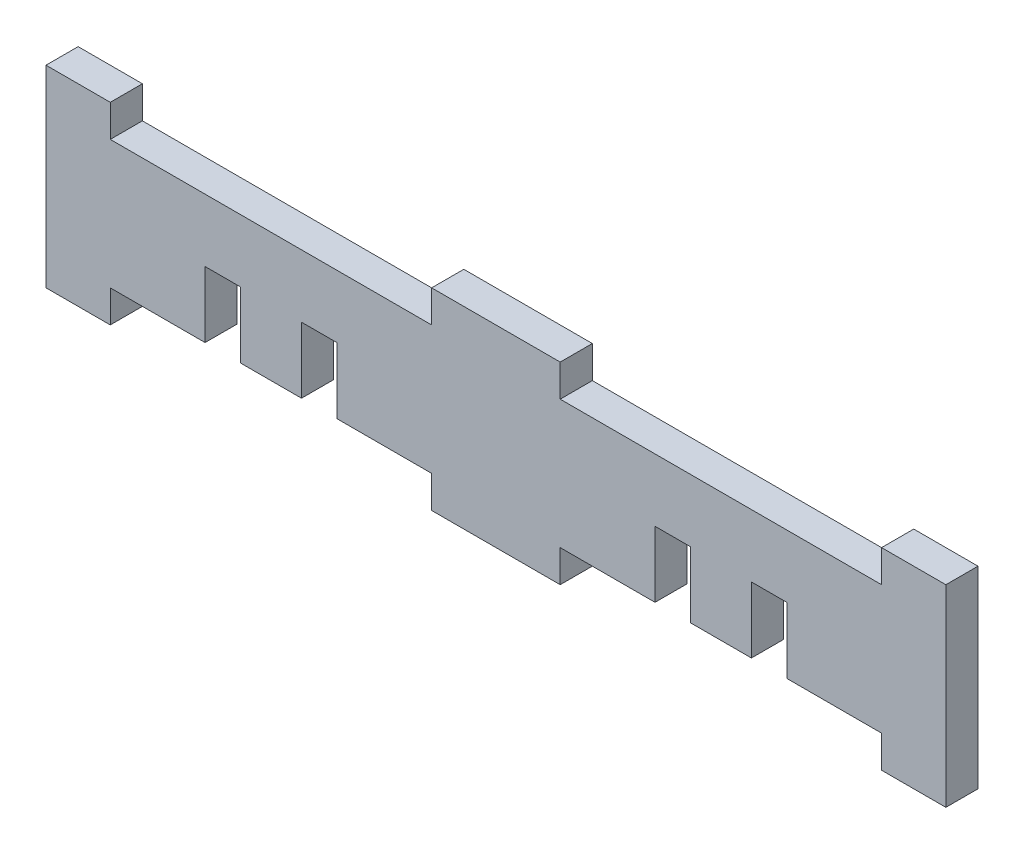
SolidWorks part; units mm, degrees
ref_plane "Front Plane" through (0, 0, 0) normal (0, 0, 1) x (1, 0, 0)
ref_plane "Top Plane" through (0, 0, 0) normal (0, 1, 0) x (1, 0, 0)
ref_plane "Right Plane" through (0, 0, 0) normal (1, 0, 0) x (0, 0, -1)
sketch "Model" plane through (0, 0, 0) normal (0, 0, 1) x (1, 0, 0)
  line L0 (-1336.4543, -207.297) -> (-1321.7043, -207.297)
  line L1 (-1386.2043, -207.297) -> (-1376.7043, -207.297)
  line L2 (-1316.2043, -207.297) -> (-1316.2043, -197.047)
  line L3 (-1276.4543, -182.297) -> (-1286.4543, -182.297)
  line L4 (-1316.2043, -197.047) -> (-1321.7043, -197.047)
  line L5 (-1306.7043, -197.047) -> (-1306.7043, -207.297)
  line L6 (-1301.2043, -197.047) -> (-1306.7043, -197.047)
  line L7 (-1371.2043, -207.297) -> (-1356.4543, -207.297)
  line L8 (-1276.4543, -212.297) -> (-1276.4543, -182.297)
  line L9 (-1356.4543, -207.297) -> (-1356.4543, -212.297)
  line L10 (-1406.4543, -182.297) -> (-1416.4543, -182.297)
  line L11 (-1376.7043, -197.047) -> (-1376.7043, -207.297)
  line L12 (-1391.7043, -197.047) -> (-1391.7043, -207.297)
  line L13 (-1286.4543, -187.297) -> (-1336.4543, -187.297)
  line L14 (-1286.4543, -182.297) -> (-1286.4543, -187.297)
  line L15 (-1406.4543, -207.297) -> (-1391.7043, -207.297)
  line L16 (-1301.2043, -207.297) -> (-1301.2043, -197.047)
  line L17 (-1406.4543, -187.297) -> (-1406.4543, -182.297)
  line L18 (-1336.4543, -182.297) -> (-1356.4543, -182.297)
  line L19 (-1286.4543, -212.297) -> (-1276.4543, -212.297)
  line L20 (-1386.2043, -197.047) -> (-1391.7043, -197.047)
  line L21 (-1371.2043, -207.297) -> (-1371.2043, -197.047)
  line L22 (-1356.4543, -187.297) -> (-1406.4543, -187.297)
  line L23 (-1416.4543, -212.297) -> (-1406.4543, -212.297)
  line L24 (-1356.4543, -182.297) -> (-1356.4543, -187.297)
  line L25 (-1356.4543, -212.297) -> (-1336.4543, -212.297)
  line L26 (-1301.2043, -207.297) -> (-1286.4543, -207.297)
  line L27 (-1371.2043, -197.047) -> (-1376.7043, -197.047)
  line L28 (-1321.7043, -197.047) -> (-1321.7043, -207.297)
  line L29 (-1316.2043, -207.297) -> (-1306.7043, -207.297)
  line L30 (-1286.4543, -207.297) -> (-1286.4543, -212.297)
  line L31 (-1336.4543, -187.297) -> (-1336.4543, -182.297)
  line L32 (-1416.4543, -182.297) -> (-1416.4543, -212.297)
  line L33 (-1406.4543, -212.297) -> (-1406.4543, -207.297)
  line L34 (-1386.2043, -207.297) -> (-1386.2043, -197.047)
  line L35 (-1336.4543, -212.297) -> (-1336.4543, -207.297)
  line L36 (-1411.4543, -205.297) -> (-1411.4543, -210.297)
  line L37 (-1412.4543, -208.297) -> (-1411.4543, -210.297)
  line L38 (-1410.4543, -208.297) -> (-1411.4543, -210.297)
  line L39 (-1408.3949, -204.2749) -> (-1407.783, -201.7779)
  line L40 (-1414.0103, -199.996) -> (-1413.6489, -200.1014)
  line L41 (-1412.4518, -200.3453) -> (-1412.3909, -200.2559)
  line L42 (-1412.1474, -200.0983) -> (-1412.3909, -200.2559)
  line L43 (-1413.3475, -200.3455) -> (-1413.4078, -200.2567)
  line L44 (-1414.4513, -199.9609) -> (-1414.0103, -199.996)
  line L45 (-1409.5188, -199.9609) -> (-1409.0443, -201.7779)
  line L46 (-1411.7915, -199.9953) -> (-1411.3482, -199.9609)
  line L47 (-1411.3482, -204.2688) -> (-1411.7821, -204.233)
  line L48 (-1412.3909, -203.9692) -> (-1412.1474, -204.1253)
  line L49 (-1410.3304, -204.2688) -> (-1411.3482, -204.2688)
  line L50 (-1412.1474, -200.0983) -> (-1411.7915, -199.9953)
  line L51 (-1412.4721, -203.7881) -> (-1412.4518, -203.8817)
  line L52 (-1411.3482, -199.9609) -> (-1410.3304, -199.9609)
  line L53 (-1412.4721, -203.7881) -> (-1412.4721, -200.4417)
  line L54 (-1413.4078, -200.2567) -> (-1413.6489, -200.1014)
  line L55 (-1412.1474, -204.1253) -> (-1411.7821, -204.233)
  line L56 (-1413.3274, -200.4417) -> (-1413.3475, -200.3455)
  line L57 (-1412.3909, -203.9692) -> (-1412.4518, -203.8817)
  line L58 (-1410.3304, -204.2688) -> (-1410.3304, -199.9609)
  line L59 (-1409.0443, -201.7779) -> (-1408.3949, -204.2749)
  line L60 (-1409.0443, -201.7779) -> (-1407.783, -201.7779)
  line L61 (-1412.4721, -200.4417) -> (-1412.4518, -200.3453)
  line L62 (-1414.8923, -199.996) -> (-1414.4513, -199.9609)
  line L63 (-1415.5551, -202.2485) -> (-1415.5752, -202.1523)
  line L64 (-1415.5752, -200.4417) -> (-1415.5551, -200.3455)
  line L65 (-1415.5003, -204.2688) -> (-1413.3274, -204.2688)
  line L66 (-1415.4948, -200.2567) -> (-1415.2536, -200.1014)
  line L67 (-1415.5551, -200.3455) -> (-1415.4948, -200.2567)
  line L68 (-1413.7769, -202.5332) -> (-1414.4513, -202.6331)
  line L69 (-1415.4948, -202.3373) -> (-1415.5551, -202.2485)
  line L70 (-1413.3274, -204.2688) -> (-1413.3274, -202.1523)
  line L71 (-1414.8923, -202.598) -> (-1415.2536, -202.4926)
  line L72 (-1414.4513, -202.6331) -> (-1414.8923, -202.598)
  line L73 (-1415.2536, -200.1014) -> (-1414.8923, -199.996)
  line L74 (-1413.3274, -202.1523) -> (-1413.5459, -202.4068)
  line L75 (-1415.5752, -202.1523) -> (-1415.5752, -200.4417)
  line L76 (-1413.5459, -202.4068) -> (-1413.7769, -202.5332)
  line L77 (-1415.2536, -202.4926) -> (-1415.4948, -202.3373)
  line L78 (-1407.783, -201.7779) -> (-1407.3335, -199.9609)
  line L79 (-1284.8892, -189.3321) -> (-1284.4482, -189.297)
  line L80 (-1284.4482, -189.297) -> (-1284.0073, -189.3321)
  line L81 (-1278.398, -193.611) -> (-1277.7861, -191.114)
  line L82 (-1279.5219, -189.297) -> (-1279.0474, -191.114)
  line L83 (-1279.0474, -191.114) -> (-1277.7861, -191.114)
  line L84 (-1279.0474, -191.114) -> (-1278.398, -193.611)
  line L85 (-1283.5429, -191.7429) -> (-1283.3243, -191.4884)
  line L86 (-1283.7739, -191.8693) -> (-1284.4482, -191.9692)
  line L87 (-1283.3243, -193.6049) -> (-1285.4972, -193.6049)
  line L88 (-1283.3444, -189.6816) -> (-1283.4047, -189.5928)
  line L89 (-1283.6459, -189.4375) -> (-1284.0073, -189.3321)
  line L90 (-1285.5521, -191.5846) -> (-1285.4918, -191.6734)
  line L91 (-1285.4918, -191.6734) -> (-1285.2506, -191.8287)
  line L92 (-1283.3243, -191.4884) -> (-1283.3243, -193.6049)
  line L93 (-1283.3444, -189.6816) -> (-1283.3243, -189.7778)
  line L94 (-1283.6459, -189.4375) -> (-1283.4047, -189.5928)
  line L95 (-1283.5429, -191.7429) -> (-1283.7739, -191.8693)
  line L96 (-1284.4482, -191.9692) -> (-1284.8892, -191.9341)
  line L97 (-1285.5721, -191.4884) -> (-1285.5721, -189.7778)
  line L98 (-1285.5521, -189.6816) -> (-1285.5721, -189.7778)
  line L99 (-1285.5721, -191.4884) -> (-1285.5521, -191.5846)
  line L100 (-1285.2506, -191.8287) -> (-1284.8892, -191.9341)
  line L101 (-1277.7861, -191.114) -> (-1277.3365, -189.297)
  line L102 (-1285.4918, -189.5928) -> (-1285.2506, -189.4375)
  line L103 (-1285.2506, -189.4375) -> (-1284.8892, -189.3321)
  line L104 (-1285.5521, -189.6816) -> (-1285.4918, -189.5928)
  line L105 (-1280.7861, -191.114) -> (-1280.3365, -189.297)
  line L106 (-1282.0474, -191.114) -> (-1281.398, -193.611)
  line L107 (-1281.398, -193.611) -> (-1280.7861, -191.114)
  line L108 (-1282.5219, -189.297) -> (-1282.0474, -191.114)
  line L109 (-1282.0474, -191.114) -> (-1280.7861, -191.114)
  line L110 (-1281.4543, -189.297) -> (-1281.4543, -184.297)
  line L111 (-1280.4543, -186.297) -> (-1281.4543, -184.297)
  line L112 (-1282.4543, -186.297) -> (-1281.4543, -184.297)
  line L113 (-1414.8892, -189.3321) -> (-1414.4482, -189.297)
  line L114 (-1414.4482, -189.297) -> (-1414.0073, -189.3321)
  line L115 (-1408.398, -193.611) -> (-1407.7861, -191.114)
  line L116 (-1409.5219, -189.297) -> (-1409.0474, -191.114)
  line L117 (-1409.0474, -191.114) -> (-1407.7861, -191.114)
  line L118 (-1409.0474, -191.114) -> (-1408.398, -193.611)
  line L119 (-1413.5429, -191.7429) -> (-1413.3243, -191.4884)
  line L120 (-1413.7739, -191.8693) -> (-1414.4482, -191.9692)
  line L121 (-1413.3243, -193.6049) -> (-1415.4972, -193.6049)
  line L122 (-1413.3444, -189.6816) -> (-1413.4047, -189.5928)
  line L123 (-1413.6459, -189.4375) -> (-1414.0073, -189.3321)
  line L124 (-1415.5521, -191.5846) -> (-1415.4918, -191.6734)
  line L125 (-1415.4918, -191.6734) -> (-1415.2506, -191.8287)
  line L126 (-1413.3243, -191.4884) -> (-1413.3243, -193.6049)
  line L127 (-1413.3444, -189.6816) -> (-1413.3243, -189.7778)
  line L128 (-1413.6459, -189.4375) -> (-1413.4047, -189.5928)
  line L129 (-1413.5429, -191.7429) -> (-1413.7739, -191.8693)
  line L130 (-1414.4482, -191.9692) -> (-1414.8892, -191.9341)
  line L131 (-1415.5721, -191.4884) -> (-1415.5721, -189.7778)
  line L132 (-1415.5521, -189.6816) -> (-1415.5721, -189.7778)
  line L133 (-1415.5721, -191.4884) -> (-1415.5521, -191.5846)
  line L134 (-1415.2506, -191.8287) -> (-1414.8892, -191.9341)
  line L135 (-1407.7861, -191.114) -> (-1407.3365, -189.297)
  line L136 (-1415.4918, -189.5928) -> (-1415.2506, -189.4375)
  line L137 (-1415.2506, -189.4375) -> (-1414.8892, -189.3321)
  line L138 (-1415.5521, -189.6816) -> (-1415.4918, -189.5928)
  line L139 (-1410.7861, -191.114) -> (-1410.3365, -189.297)
  line L140 (-1412.0474, -191.114) -> (-1411.398, -193.611)
  line L141 (-1411.398, -193.611) -> (-1410.7861, -191.114)
  line L142 (-1412.5219, -189.297) -> (-1412.0474, -191.114)
  line L143 (-1412.0474, -191.114) -> (-1410.7861, -191.114)
  line L144 (-1411.4543, -189.297) -> (-1411.4543, -184.297)
  line L145 (-1410.4543, -186.297) -> (-1411.4543, -184.297)
  line L146 (-1412.4543, -186.297) -> (-1411.4543, -184.297)
  line L147 (-1281.4543, -205.297) -> (-1281.4543, -210.297)
  line L148 (-1282.4543, -208.297) -> (-1281.4543, -210.297)
  line L149 (-1280.4543, -208.297) -> (-1281.4543, -210.297)
  line L150 (-1278.3949, -204.2749) -> (-1277.783, -201.7779)
  line L151 (-1284.0103, -199.996) -> (-1283.6489, -200.1014)
  line L152 (-1282.4518, -200.3453) -> (-1282.3909, -200.2559)
  line L153 (-1282.1474, -200.0983) -> (-1282.3909, -200.2559)
  line L154 (-1283.3475, -200.3455) -> (-1283.4078, -200.2567)
  line L155 (-1284.4513, -199.9609) -> (-1284.0103, -199.996)
  line L156 (-1279.5188, -199.9609) -> (-1279.0443, -201.7779)
  line L157 (-1281.7915, -199.9953) -> (-1281.3482, -199.9609)
  line L158 (-1281.3482, -204.2688) -> (-1281.7821, -204.233)
  line L159 (-1282.3909, -203.9692) -> (-1282.1474, -204.1253)
  line L160 (-1280.3304, -204.2688) -> (-1281.3482, -204.2688)
  line L161 (-1282.1474, -200.0983) -> (-1281.7915, -199.9953)
  line L162 (-1282.4721, -203.7881) -> (-1282.4518, -203.8817)
  line L163 (-1281.3482, -199.9609) -> (-1280.3304, -199.9609)
  line L164 (-1282.4721, -203.7881) -> (-1282.4721, -200.4417)
  line L165 (-1283.4078, -200.2567) -> (-1283.6489, -200.1014)
  line L166 (-1282.1474, -204.1253) -> (-1281.7821, -204.233)
  line L167 (-1283.3274, -200.4417) -> (-1283.3475, -200.3455)
  line L168 (-1282.3909, -203.9692) -> (-1282.4518, -203.8817)
  line L169 (-1280.3304, -204.2688) -> (-1280.3304, -199.9609)
  line L170 (-1279.0443, -201.7779) -> (-1278.3949, -204.2749)
  line L171 (-1279.0443, -201.7779) -> (-1277.783, -201.7779)
  line L172 (-1282.4721, -200.4417) -> (-1282.4518, -200.3453)
  line L173 (-1284.8923, -199.996) -> (-1284.4513, -199.9609)
  line L174 (-1285.5551, -202.2485) -> (-1285.5752, -202.1523)
  line L175 (-1285.5752, -200.4417) -> (-1285.5551, -200.3455)
  line L176 (-1285.5003, -204.2688) -> (-1283.3274, -204.2688)
  line L177 (-1285.4948, -200.2567) -> (-1285.2536, -200.1014)
  line L178 (-1285.5551, -200.3455) -> (-1285.4948, -200.2567)
  line L179 (-1283.7769, -202.5332) -> (-1284.4513, -202.6331)
  line L180 (-1285.4948, -202.3373) -> (-1285.5551, -202.2485)
  line L181 (-1283.3274, -204.2688) -> (-1283.3274, -202.1523)
  line L182 (-1284.8923, -202.598) -> (-1285.2536, -202.4926)
  line L183 (-1284.4513, -202.6331) -> (-1284.8923, -202.598)
  line L184 (-1285.2536, -200.1014) -> (-1284.8923, -199.996)
  line L185 (-1283.3274, -202.1523) -> (-1283.5459, -202.4068)
  line L186 (-1285.5752, -202.1523) -> (-1285.5752, -200.4417)
  line L187 (-1283.5459, -202.4068) -> (-1283.7769, -202.5332)
  line L188 (-1285.2536, -202.4926) -> (-1285.4948, -202.3373)
  line L189 (-1277.783, -201.7779) -> (-1277.3335, -199.9609)
  line L190 (-1318.9543, -189.797) -> (-1318.9543, -194.797)
  line L191 (-1319.9543, -192.797) -> (-1318.9543, -194.797)
  line L192 (-1317.9543, -192.797) -> (-1318.9543, -194.797)
  line L193 (-1310.3564, -193.7202) -> (-1310.4162, -193.8084)
  line L194 (-1312.5032, -193.8052) -> (-1312.2597, -193.9614)
  line L195 (-1311.0218, -194.069) -> (-1310.655, -193.9614)
  line L196 (-1312.5641, -193.7178) -> (-1312.5032, -193.8052)
  line L197 (-1309.0504, -191.614) -> (-1308.401, -194.111)
  line L198 (-1311.8944, -194.069) -> (-1311.4604, -194.1049)
  line L199 (-1312.2597, -193.9614) -> (-1311.8944, -194.069)
  line L200 (-1309.5249, -189.797) -> (-1309.0504, -191.614)
  line L201 (-1311.4604, -194.1049) -> (-1311.0218, -194.069)
  line L202 (-1307.7891, -191.6197) -> (-1307.3396, -189.797)
  line L203 (-1312.5641, -193.7178) -> (-1312.5843, -193.6242)
  line L204 (-1310.3564, -193.7202) -> (-1310.3365, -193.6242)
  line L205 (-1308.401, -194.111) -> (-1307.7891, -191.6197)
  line L206 (-1307.7891, -191.6197) -> (-1309.0504, -191.614)
  line L207 (-1310.655, -193.9614) -> (-1310.4162, -193.8084)
  line L208 (-1310.4162, -190.0889) -> (-1310.655, -189.9343)
  line L209 (-1313.3274, -191.9884) -> (-1313.3274, -194.1049)
  line L210 (-1314.8923, -189.8321) -> (-1314.4513, -189.797)
  line L211 (-1310.655, -189.9343) -> (-1311.0156, -189.8313)
  line L212 (-1314.4513, -189.797) -> (-1314.0103, -189.8321)
  line L213 (-1312.5843, -193.6242) -> (-1312.5843, -193.3182)
  line L214 (-1310.3564, -190.179) -> (-1310.4162, -190.0889)
  line L215 (-1315.5551, -190.1816) -> (-1315.5752, -190.2778)
  line L216 (-1313.7769, -192.3693) -> (-1313.5459, -192.2429)
  line L217 (-1311.9038, -189.8313) -> (-1312.2597, -189.9343)
  line L218 (-1315.2537, -192.3287) -> (-1315.4948, -192.1734)
  line L219 (-1315.5752, -191.9884) -> (-1315.5752, -190.2778)
  line L220 (-1315.5551, -190.1816) -> (-1315.4948, -190.0928)
  line L221 (-1313.6489, -189.9375) -> (-1314.0103, -189.8321)
  line L222 (-1310.3365, -193.6242) -> (-1310.3365, -190.2778)
  line L223 (-1315.5752, -191.9884) -> (-1315.5551, -192.0846)
  line L224 (-1312.5843, -190.2778) -> (-1312.5843, -190.5837)
  line L225 (-1311.0156, -189.8313) -> (-1311.4604, -189.797)
  line L226 (-1315.5003, -194.1049) -> (-1313.3274, -194.1049)
  line L227 (-1315.5551, -192.0846) -> (-1315.4948, -192.1734)
  line L228 (-1314.8923, -189.8321) -> (-1315.2537, -189.9375)
  line L229 (-1313.3475, -190.1816) -> (-1313.3274, -190.2778)
  line L230 (-1312.5641, -190.1814) -> (-1312.5843, -190.2778)
  line L231 (-1313.4078, -190.0928) -> (-1313.3475, -190.1816)
  line L232 (-1312.2597, -189.9343) -> (-1312.5032, -190.092)
  line L233 (-1313.4078, -190.0928) -> (-1313.6489, -189.9375)
  line L234 (-1311.4604, -189.797) -> (-1311.9038, -189.8313)
  line L235 (-1314.4513, -192.4692) -> (-1313.7769, -192.3693)
  line L236 (-1314.8923, -192.4341) -> (-1314.4513, -192.4692)
  line L237 (-1310.3365, -190.2778) -> (-1310.3564, -190.179)
  line L238 (-1313.5459, -192.2429) -> (-1313.3274, -191.9884)
  line L239 (-1312.5032, -190.092) -> (-1312.5641, -190.1814)
  line L240 (-1315.2537, -192.3287) -> (-1314.8923, -192.4341)
  line L241 (-1315.2537, -189.9375) -> (-1315.4948, -190.0928)
  line L242 (-1303.9543, -189.797) -> (-1303.9543, -194.797)
  line L243 (-1304.9543, -192.797) -> (-1303.9543, -194.797)
  line L244 (-1302.9543, -192.797) -> (-1303.9543, -194.797)
  line L245 (-1388.9543, -189.797) -> (-1388.9543, -194.797)
  line L246 (-1389.9543, -192.797) -> (-1388.9543, -194.797)
  line L247 (-1387.9543, -192.797) -> (-1388.9543, -194.797)
  line L248 (-1380.3564, -193.7202) -> (-1380.4161, -193.8084)
  line L249 (-1382.5032, -193.8052) -> (-1382.2596, -193.9614)
  line L250 (-1381.0218, -194.069) -> (-1380.655, -193.9614)
  line L251 (-1382.564, -193.7178) -> (-1382.5032, -193.8052)
  line L252 (-1379.0504, -191.614) -> (-1378.401, -194.111)
  line L253 (-1381.8944, -194.069) -> (-1381.4604, -194.1049)
  line L254 (-1382.2596, -193.9614) -> (-1381.8944, -194.069)
  line L255 (-1379.5249, -189.797) -> (-1379.0504, -191.614)
  line L256 (-1381.4604, -194.1049) -> (-1381.0218, -194.069)
  line L257 (-1377.7891, -191.6197) -> (-1377.3396, -189.797)
  line L258 (-1382.564, -193.7178) -> (-1382.5843, -193.6242)
  line L259 (-1380.3564, -193.7202) -> (-1380.3365, -193.6242)
  line L260 (-1378.401, -194.111) -> (-1377.7891, -191.6197)
  line L261 (-1377.7891, -191.6197) -> (-1379.0504, -191.614)
  line L262 (-1380.655, -193.9614) -> (-1380.4161, -193.8084)
  line L263 (-1380.4161, -190.0889) -> (-1380.655, -189.9343)
  line L264 (-1383.3274, -191.9884) -> (-1383.3274, -194.1049)
  line L265 (-1384.8923, -189.8321) -> (-1384.4513, -189.797)
  line L266 (-1380.655, -189.9343) -> (-1381.0156, -189.8313)
  line L267 (-1384.4513, -189.797) -> (-1384.0103, -189.8321)
  line L268 (-1382.5843, -193.6242) -> (-1382.5843, -193.3182)
  line L269 (-1380.3564, -190.179) -> (-1380.4161, -190.0889)
  line L270 (-1385.5551, -190.1816) -> (-1385.5752, -190.2778)
  line L271 (-1383.7769, -192.3693) -> (-1383.5459, -192.2429)
  line L272 (-1381.9038, -189.8313) -> (-1382.2596, -189.9343)
  line L273 (-1385.2536, -192.3287) -> (-1385.4948, -192.1734)
  line L274 (-1385.5752, -191.9884) -> (-1385.5752, -190.2778)
  line L275 (-1385.5551, -190.1816) -> (-1385.4948, -190.0928)
  line L276 (-1383.6489, -189.9375) -> (-1384.0103, -189.8321)
  line L277 (-1380.3365, -193.6242) -> (-1380.3365, -190.2778)
  line L278 (-1385.5752, -191.9884) -> (-1385.5551, -192.0846)
  line L279 (-1382.5843, -190.2778) -> (-1382.5843, -190.5837)
  line L280 (-1381.0156, -189.8313) -> (-1381.4604, -189.797)
  line L281 (-1385.5003, -194.1049) -> (-1383.3274, -194.1049)
  line L282 (-1385.5551, -192.0846) -> (-1385.4948, -192.1734)
  line L283 (-1384.8923, -189.8321) -> (-1385.2536, -189.9375)
  line L284 (-1383.3475, -190.1816) -> (-1383.3274, -190.2778)
  line L285 (-1382.564, -190.1814) -> (-1382.5843, -190.2778)
  line L286 (-1383.4078, -190.0928) -> (-1383.3475, -190.1816)
  line L287 (-1382.2596, -189.9343) -> (-1382.5032, -190.092)
  line L288 (-1383.4078, -190.0928) -> (-1383.6489, -189.9375)
  line L289 (-1381.4604, -189.797) -> (-1381.9038, -189.8313)
  line L290 (-1384.4513, -192.4692) -> (-1383.7769, -192.3693)
  line L291 (-1384.8923, -192.4341) -> (-1384.4513, -192.4692)
  line L292 (-1380.3365, -190.2778) -> (-1380.3564, -190.179)
  line L293 (-1383.5459, -192.2429) -> (-1383.3274, -191.9884)
  line L294 (-1382.5032, -190.092) -> (-1382.564, -190.1814)
  line L295 (-1385.2536, -192.3287) -> (-1384.8923, -192.4341)
  line L296 (-1385.2536, -189.9375) -> (-1385.4948, -190.0928)
  line L297 (-1373.9543, -189.797) -> (-1373.9543, -194.797)
  line L298 (-1374.9543, -192.797) -> (-1373.9543, -194.797)
  line L299 (-1372.9543, -192.797) -> (-1373.9543, -194.797)
  line L300 (-1351.4543, -205.297) -> (-1351.4543, -210.297)
  line L301 (-1352.4543, -208.297) -> (-1351.4543, -210.297)
  line L302 (-1350.4543, -208.297) -> (-1351.4543, -210.297)
  line L303 (-1341.7741, -209.611) -> (-1341.1622, -207.114)
  line L304 (-1347.3895, -205.3321) -> (-1347.0281, -205.4375)
  line L305 (-1345.831, -205.6814) -> (-1345.7701, -205.592)
  line L306 (-1345.5266, -205.4343) -> (-1345.7701, -205.592)
  line L307 (-1346.7266, -205.6816) -> (-1346.7869, -205.5928)
  line L308 (-1347.8304, -205.297) -> (-1347.3895, -205.3321)
  line L309 (-1342.898, -205.297) -> (-1342.4235, -207.114)
  line L310 (-1345.1707, -205.3313) -> (-1344.7274, -205.297)
  line L311 (-1344.7274, -209.6049) -> (-1345.1613, -209.569)
  line L312 (-1345.7701, -209.3052) -> (-1345.5266, -209.4614)
  line L313 (-1343.7096, -209.6049) -> (-1344.7274, -209.6049)
  line L314 (-1345.5266, -205.4343) -> (-1345.1707, -205.3313)
  line L315 (-1345.8513, -209.1242) -> (-1345.831, -209.2178)
  line L316 (-1344.7274, -205.297) -> (-1343.7096, -205.297)
  line L317 (-1345.8513, -209.1242) -> (-1345.8513, -205.7778)
  line L318 (-1346.7869, -205.5928) -> (-1347.0281, -205.4375)
  line L319 (-1345.5266, -209.4614) -> (-1345.1613, -209.569)
  line L320 (-1346.7065, -205.7778) -> (-1346.7266, -205.6816)
  line L321 (-1345.7701, -209.3052) -> (-1345.831, -209.2178)
  line L322 (-1343.7096, -209.6049) -> (-1343.7096, -205.297)
  line L323 (-1342.4235, -207.114) -> (-1341.7741, -209.611)
  line L324 (-1342.4235, -207.114) -> (-1341.1622, -207.114)
  line L325 (-1345.8513, -205.7778) -> (-1345.831, -205.6814)
  line L326 (-1348.2714, -205.3321) -> (-1347.8304, -205.297)
  line L327 (-1348.9342, -207.5846) -> (-1348.9543, -207.4884)
  line L328 (-1348.9543, -205.7778) -> (-1348.9342, -205.6816)
  line L329 (-1348.8794, -209.6049) -> (-1346.7065, -209.6049)
  line L330 (-1348.874, -205.5928) -> (-1348.6328, -205.4375)
  line L331 (-1348.9342, -205.6816) -> (-1348.874, -205.5928)
  line L332 (-1347.1561, -207.8693) -> (-1347.8304, -207.9692)
  line L333 (-1348.874, -207.6734) -> (-1348.9342, -207.5846)
  line L334 (-1346.7065, -209.6049) -> (-1346.7065, -207.4884)
  line L335 (-1348.2714, -207.9341) -> (-1348.6328, -207.8287)
  line L336 (-1347.8304, -207.9692) -> (-1348.2714, -207.9341)
  line L337 (-1348.6328, -205.4375) -> (-1348.2714, -205.3321)
  line L338 (-1346.7065, -207.4884) -> (-1346.9251, -207.7429)
  line L339 (-1348.9543, -207.4884) -> (-1348.9543, -205.7778)
  line L340 (-1346.9251, -207.7429) -> (-1347.1561, -207.8693)
  line L341 (-1348.6328, -207.8287) -> (-1348.874, -207.6734)
  line L342 (-1341.1622, -207.114) -> (-1340.7126, -205.297)
  line L343 (-1348.2714, -184.3321) -> (-1347.8304, -184.297)
  line L344 (-1347.8304, -184.297) -> (-1347.3895, -184.3321)
  line L345 (-1341.7802, -188.611) -> (-1341.1683, -186.114)
  line L346 (-1342.9041, -184.297) -> (-1342.4296, -186.114)
  line L347 (-1342.4296, -186.114) -> (-1341.1683, -186.114)
  line L348 (-1342.4296, -186.114) -> (-1341.7802, -188.611)
  line L349 (-1346.9251, -186.7429) -> (-1346.7065, -186.4884)
  line L350 (-1347.1561, -186.8693) -> (-1347.8304, -186.9692)
  line L351 (-1346.7065, -188.6049) -> (-1348.8794, -188.6049)
  line L352 (-1346.7266, -184.6816) -> (-1346.7869, -184.5928)
  line L353 (-1347.0281, -184.4375) -> (-1347.3895, -184.3321)
  line L354 (-1348.9342, -186.5846) -> (-1348.874, -186.6734)
  line L355 (-1348.874, -186.6734) -> (-1348.6328, -186.8287)
  line L356 (-1346.7065, -186.4884) -> (-1346.7065, -188.6049)
  line L357 (-1346.7266, -184.6816) -> (-1346.7065, -184.7778)
  line L358 (-1347.0281, -184.4375) -> (-1346.7869, -184.5928)
  line L359 (-1346.9251, -186.7429) -> (-1347.1561, -186.8693)
  line L360 (-1347.8304, -186.9692) -> (-1348.2714, -186.9341)
  line L361 (-1348.9543, -186.4884) -> (-1348.9543, -184.7778)
  line L362 (-1348.9342, -184.6816) -> (-1348.9543, -184.7778)
  line L363 (-1348.9543, -186.4884) -> (-1348.9342, -186.5846)
  line L364 (-1348.6328, -186.8287) -> (-1348.2714, -186.9341)
  line L365 (-1341.1683, -186.114) -> (-1340.7187, -184.297)
  line L366 (-1348.874, -184.5928) -> (-1348.6328, -184.4375)
  line L367 (-1348.6328, -184.4375) -> (-1348.2714, -184.3321)
  line L368 (-1348.9342, -184.6816) -> (-1348.874, -184.5928)
  line L369 (-1344.1683, -186.114) -> (-1343.7187, -184.297)
  line L370 (-1345.4296, -186.114) -> (-1344.7802, -188.611)
  line L371 (-1344.7802, -188.611) -> (-1344.1683, -186.114)
  line L372 (-1345.9041, -184.297) -> (-1345.4296, -186.114)
  line L373 (-1345.4296, -186.114) -> (-1344.1683, -186.114)
  line L374 (-1351.4543, -189.297) -> (-1351.4543, -184.297)
  line L375 (-1350.4543, -186.297) -> (-1351.4543, -184.297)
  line L376 (-1352.4543, -186.297) -> (-1351.4543, -184.297)
  line L377 (-1339.1928, -198.3523) -> (-1340.4166, -203.3349)
  line L378 (-1340.4166, -203.3349) -> (-1341.7153, -198.3523)
  line L379 (-1341.7153, -198.3523) -> (-1339.1928, -198.3523)
  line L380 (-1342.6644, -194.7069) -> (-1340.4166, -203.3349)
  line L381 (-1340.4166, -203.3349) -> (-1338.2937, -194.7069)
  line L382 (-1338.2937, -194.7069) -> (-1339.1928, -198.3408)
  line L383 (-1339.1928, -198.3408) -> (-1341.7153, -198.3408)
  line L384 (-1341.7153, -198.3408) -> (-1342.6644, -194.7069)
  line L385 (-1344.2876, -194.7069) -> (-1344.2876, -199.1025)
  line L386 (-1344.2876, -199.1025) -> (-1346.3231, -199.1025)
  line L387 (-1346.3231, -199.1025) -> (-1347.4376, -198.9652)
  line L388 (-1347.4376, -198.9652) -> (-1348.1088, -198.7529)
  line L389 (-1348.1088, -198.7529) -> (-1348.4554, -198.4844)
  line L390 (-1348.4554, -198.4844) -> (-1348.5709, -198.1785)
  line L391 (-1348.5709, -198.1785) -> (-1348.5709, -195.6685)
  line L392 (-1348.5709, -195.6685) -> (-1348.5295, -195.471)
  line L393 (-1348.5295, -195.471) -> (-1348.4054, -195.2907)
  line L394 (-1348.4054, -195.2907) -> (-1347.909, -194.9816)
  line L395 (-1347.909, -194.9816) -> (-1347.1879, -194.7756)
  line L396 (-1347.1879, -194.7756) -> (-1346.3231, -194.7069)
  line L397 (-1346.3231, -194.7069) -> (-1344.2876, -194.7069)
  line L398 (-1344.2876, -203.3227) -> (-1344.2876, -194.7069)
  line L399 (-1344.2876, -194.7069) -> (-1346.3231, -194.7069)
  line L400 (-1346.3231, -194.7069) -> (-1347.1879, -194.7755)
  line L401 (-1347.1879, -194.7755) -> (-1347.909, -194.9815)
  line L402 (-1347.909, -194.9815) -> (-1348.4054, -195.2906)
  line L403 (-1348.4054, -195.2906) -> (-1348.5295, -195.4709)
  line L404 (-1348.5295, -195.4709) -> (-1348.5709, -195.6684)
  line L405 (-1348.5709, -195.6684) -> (-1348.5709, -198.1782)
  line L406 (-1348.5709, -198.1782) -> (-1348.4554, -198.4841)
  line L407 (-1348.4554, -198.4841) -> (-1348.1088, -198.7525)
  line L408 (-1348.1088, -198.7525) -> (-1347.4376, -198.9648)
  line L409 (-1347.4376, -198.9648) -> (-1346.3231, -199.1022)
  line L410 (-1346.3231, -199.1022) -> (-1347.4251, -199.2301)
  line L411 (-1347.4251, -199.2301) -> (-1348.1088, -199.4393)
  line L412 (-1348.1088, -199.4393) -> (-1348.4554, -199.7172)
  line L413 (-1348.4554, -199.7172) -> (-1348.5709, -200.0262)
  line L414 (-1348.5709, -200.0262) -> (-1348.5709, -202.3612)
  line L415 (-1348.5709, -202.3612) -> (-1348.5295, -202.5485)
  line L416 (-1348.5295, -202.5485) -> (-1348.4054, -202.7234)
  line L417 (-1348.4054, -202.7234) -> (-1347.909, -203.0356)
  line L418 (-1347.909, -203.0356) -> (-1347.1816, -203.2509)
  line L419 (-1347.1816, -203.2509) -> (-1346.3231, -203.3227)
  line L420 (-1346.3231, -203.3227) -> (-1344.2876, -203.3227)
  line L421 (-1346.3231, -199.1018) -> (-1344.2876, -199.1018)
  line L422 (-1344.2876, -199.1018) -> (-1344.2876, -203.3227)
  line L423 (-1344.2876, -203.3227) -> (-1346.3231, -203.3227)
  line L424 (-1346.3231, -203.3227) -> (-1347.1816, -203.2509)
  line L425 (-1347.1816, -203.2509) -> (-1347.909, -203.0355)
  line L426 (-1347.909, -203.0355) -> (-1348.4054, -202.7233)
  line L427 (-1348.4054, -202.7233) -> (-1348.5295, -202.5484)
  line L428 (-1348.5295, -202.5484) -> (-1348.5709, -202.3611)
  line L429 (-1348.5709, -202.3611) -> (-1348.5709, -200.0259)
  line L430 (-1348.5709, -200.0259) -> (-1348.4554, -199.7169)
  line L431 (-1348.4554, -199.7169) -> (-1348.1088, -199.439)
  line L432 (-1348.1088, -199.439) -> (-1347.4251, -199.2298)
  line L433 (-1347.4251, -199.2298) -> (-1346.3231, -199.1018)
  line L434 (-1352.5293, -194.7069) -> (-1351.6473, -194.7771)
  line L435 (-1351.6473, -194.7771) -> (-1350.9246, -194.9878)
  line L436 (-1350.9246, -194.9878) -> (-1350.4422, -195.2985)
  line L437 (-1350.4422, -195.2985) -> (-1350.3217, -195.476)
  line L438 (-1350.3217, -195.476) -> (-1350.2815, -195.6684)
  line L439 (-1350.2815, -195.6684) -> (-1350.3217, -195.476)
  line L440 (-1350.3217, -195.476) -> (-1350.4422, -195.2985)
  line L441 (-1350.4422, -195.2985) -> (-1350.9246, -194.9878)
  line L442 (-1354.134, -194.9878) -> (-1354.6163, -195.2985)
  line L443 (-1354.6163, -195.2985) -> (-1354.7369, -195.476)
  line L444 (-1354.7369, -195.476) -> (-1354.7771, -195.6684)
  line L445 (-1354.7771, -195.6684) -> (-1354.7771, -199.0897)
  line L446 (-1354.7771, -199.0897) -> (-1354.7369, -199.2821)
  line L447 (-1354.7369, -199.2821) -> (-1354.6163, -199.4597)
  line L448 (-1354.6163, -199.4597) -> (-1354.134, -199.7703)
  line L449 (-1354.134, -199.7703) -> (-1353.4113, -199.981)
  line L450 (-1353.4113, -199.981) -> (-1352.5293, -200.0513)
  line L451 (-1352.5293, -200.0513) -> (-1351.1806, -199.8515)
  line L452 (-1351.1806, -199.8515) -> (-1350.7185, -199.5986)
  line L453 (-1350.7185, -199.5986) -> (-1350.2815, -199.0897)
  line L454 (-1350.2815, -199.0897) -> (-1350.2815, -203.3227)
  line L455 (-1350.2815, -203.3227) -> (-1354.6272, -203.3227)
  line L456 (-1354.6272, -203.3227) -> (-1350.2815, -203.3227)
  line L457 (-1350.2815, -203.3227) -> (-1350.2815, -199.0897)
  line L458 (-1350.2815, -199.0897) -> (-1350.7185, -199.5986)
  line L459 (-1350.7185, -199.5986) -> (-1351.1806, -199.8515)
  line L460 (-1351.1806, -199.8515) -> (-1352.5293, -200.0513)
  line L461 (-1352.5293, -200.0513) -> (-1353.4113, -199.981)
  line L462 (-1353.4113, -199.981) -> (-1354.134, -199.7703)
  line L463 (-1354.134, -199.7703) -> (-1354.6163, -199.4597)
  line L464 (-1354.6163, -199.4597) -> (-1354.7369, -199.2821)
  line L465 (-1354.7369, -199.2821) -> (-1354.7771, -199.0897)
  line L466 (-1354.7771, -199.0897) -> (-1354.7771, -195.6684)
  line L467 (-1354.7771, -195.6684) -> (-1354.7369, -195.476)
  line L468 (-1354.7369, -195.476) -> (-1354.6163, -195.2985)
  line L469 (-1354.6163, -195.2985) -> (-1354.134, -194.9878)
  line L470 (-1354.134, -194.9878) -> (-1353.4113, -194.7771)
  line L471 (-1353.4113, -194.7771) -> (-1352.5293, -194.7069)
  line L472 (-1338.2937, -193.7069) -> (-1354.615, -193.7069)
  line L473 (-1340.8342, -192.7069) -> (-1340.8342, -191.6456)
  line L474 (-1338.7582, -190.5529) -> (-1338.7582, -192.7069)
  line L475 (-1338.7582, -192.7069) -> (-1339.2889, -192.7069)
  line L476 (-1347.9528, -191.6611) -> (-1347.9528, -192.7069)
  line L477 (-1339.7165, -191.6456) -> (-1340.8342, -191.6456)
  line L478 (-1338.2181, -192.7069) -> (-1338.7582, -192.7069)
  line L479 (-1339.7165, -191.6456) -> (-1339.7165, -192.7069)
  line L480 (-1339.7165, -190.5529) -> (-1339.7165, -191.6456)
  line L481 (-1341.215, -190.5529) -> (-1341.215, -192.7099)
  line L482 (-1341.7552, -190.7008) -> (-1341.7251, -190.7452)
  line L483 (-1341.7251, -190.7452) -> (-1341.715, -190.7933)
  line L484 (-1342.817, -191.5559) -> (-1342.7355, -191.6463)
  line L485 (-1341.7271, -191.879) -> (-1341.7634, -191.8305)
  line L486 (-1342.0565, -190.5705) -> (-1342.277, -190.5529)
  line L487 (-1341.715, -190.7933) -> (-1341.715, -190.9462)
  line L488 (-1342.7355, -191.6463) -> (-1342.6008, -191.7011)
  line L489 (-1341.8758, -190.6231) -> (-1342.0565, -190.5705)
  line L490 (-1342.8289, -192.5146) -> (-1342.7987, -192.559)
  line L491 (-1341.7552, -190.7008) -> (-1341.8758, -190.6231)
  line L492 (-1342.4975, -192.6893) -> (-1342.277, -192.7069)
  line L493 (-1341.715, -191.9327) -> (-1341.7271, -191.879)
  line L494 (-1341.715, -192.4665) -> (-1341.7251, -192.5146)
  line L495 (-1341.7634, -191.8305) -> (-1341.9086, -191.7485)
  line L496 (-1341.7251, -192.5146) -> (-1341.7552, -192.559)
  line L497 (-1342.4128, -191.7204) -> (-1342.6008, -191.7011)
  line L498 (-1342.817, -191.5559) -> (-1342.8452, -191.4301)
  line L499 (-1341.715, -192.4665) -> (-1341.715, -191.9327)
  line L500 (-1342.6781, -190.6231) -> (-1342.4975, -190.5705)
  line L501 (-1342.8452, -191.4301) -> (-1342.8389, -190.7933)
  line L502 (-1342.4975, -192.6893) -> (-1342.6781, -192.6366)
  line L503 (-1342.0565, -192.6893) -> (-1342.277, -192.7069)
  line L504 (-1342.0721, -191.729) -> (-1342.4128, -191.7204)
  line L505 (-1342.277, -190.5529) -> (-1342.4975, -190.5705)
  line L506 (-1342.8289, -192.5146) -> (-1342.8389, -192.4665)
  line L507 (-1341.9086, -191.7485) -> (-1342.0721, -191.729)
  line L508 (-1342.0565, -192.6893) -> (-1341.8758, -192.6366)
  line L509 (-1342.6781, -190.6231) -> (-1342.7987, -190.7008)
  line L510 (-1342.7987, -190.7008) -> (-1342.8289, -190.7452)
  line L511 (-1342.8289, -190.7452) -> (-1342.8389, -190.7933)
  line L512 (-1341.8758, -192.6366) -> (-1341.7552, -192.559)
  line L513 (-1342.7987, -192.559) -> (-1342.6781, -192.6366)
  line L514 (-1342.8389, -192.3135) -> (-1342.8389, -192.4665)
  line L515 (-1345.5828, -190.7933) -> (-1345.5728, -190.7452)
  line L516 (-1345.5728, -190.7452) -> (-1345.5426, -190.7008)
  line L517 (-1345.0209, -190.5529) -> (-1344.8004, -190.5705)
  line L518 (-1344.469, -190.7452) -> (-1344.4991, -190.7008)
  line L519 (-1345.5609, -191.5559) -> (-1345.4794, -191.6463)
  line L520 (-1345.5426, -192.559) -> (-1345.5728, -192.5146)
  line L521 (-1344.4589, -190.7933) -> (-1344.469, -190.7452)
  line L522 (-1345.5609, -191.5559) -> (-1345.5891, -191.4301)
  line L523 (-1344.4991, -192.559) -> (-1344.6197, -192.6366)
  line L524 (-1344.816, -191.729) -> (-1344.6525, -191.7485)
  line L525 (-1344.5073, -191.8305) -> (-1344.6525, -191.7485)
  line L526 (-1344.6197, -190.6231) -> (-1344.8004, -190.5705)
  line L527 (-1345.5828, -190.7933) -> (-1345.5891, -191.4301)
  line L528 (-1345.1567, -191.7204) -> (-1345.3447, -191.7011)
  line L529 (-1345.2414, -190.5705) -> (-1345.422, -190.6231)
  line L530 (-1345.1567, -191.7204) -> (-1344.816, -191.729)
  line L531 (-1345.422, -192.6366) -> (-1345.2414, -192.6893)
  line L532 (-1345.0209, -190.5529) -> (-1345.2414, -190.5705)
  line L533 (-1344.4589, -191.9327) -> (-1344.4589, -192.4665)
  line L534 (-1345.4794, -191.6463) -> (-1345.3447, -191.7011)
  line L535 (-1344.469, -192.5146) -> (-1344.4991, -192.559)
  line L536 (-1345.5828, -192.4665) -> (-1345.5728, -192.5146)
  line L537 (-1344.471, -191.879) -> (-1344.4589, -191.9327)
  line L538 (-1345.422, -190.6231) -> (-1345.5426, -190.7008)
  line L539 (-1344.4589, -192.4665) -> (-1344.469, -192.5146)
  line L540 (-1344.4991, -190.7008) -> (-1344.6197, -190.6231)
  line L541 (-1345.5828, -192.3135) -> (-1345.5828, -192.4665)
  line L542 (-1345.5426, -192.559) -> (-1345.422, -192.6366)
  line L543 (-1345.2414, -192.6893) -> (-1345.0209, -192.7069)
  line L544 (-1345.0209, -192.7069) -> (-1344.8004, -192.6893)
  line L545 (-1344.8004, -192.6893) -> (-1344.6197, -192.6366)
  line L546 (-1344.471, -191.879) -> (-1344.5073, -191.8305)
  line L547 (-1351.8136, -190.7452) -> (-1351.7835, -190.7008)
  line L548 (-1349.0174, -192.7069) -> (-1347.9528, -192.7069)
  line L549 (-1353.3222, -190.7933) -> (-1353.3222, -192.6977)
  line L550 (-1347.3628, -192.6351) -> (-1347.1802, -192.6889)
  line L551 (-1346.4543, -192.7069) -> (-1346.4543, -190.5529)
  line L552 (-1347.515, -192.5133) -> (-1347.5252, -192.4665)
  line L553 (-1347.4846, -192.557) -> (-1347.3628, -192.6351)
  line L554 (-1347.9528, -190.5529) -> (-1349.0174, -190.5529)
  line L555 (-1347.3628, -190.6216) -> (-1347.1849, -190.5701)
  line L556 (-1347.515, -192.5133) -> (-1347.4846, -192.557)
  line L557 (-1351.8136, -190.7452) -> (-1351.8237, -190.7933)
  line L558 (-1347.4846, -190.7004) -> (-1347.515, -190.7451)
  line L559 (-1347.9528, -190.5529) -> (-1347.9528, -191.6611)
  line L560 (-1347.3628, -190.6216) -> (-1347.4846, -190.7004)
  line L561 (-1347.1849, -190.5701) -> (-1346.9632, -190.5529)
  line L562 (-1347.1802, -192.6889) -> (-1346.9632, -192.7069)
  line L563 (-1347.9528, -191.6611) -> (-1348.8675, -191.6611)
  line L564 (-1346.4543, -192.7069) -> (-1346.9632, -192.7069)
  line L565 (-1347.515, -190.7451) -> (-1347.5252, -190.7933)
  line L566 (-1346.4543, -190.5529) -> (-1346.9632, -190.5529)
  line L567 (-1344.4589, -190.7933) -> (-1344.4589, -190.9462)
  line L568 (-1345.9543, -192.7099) -> (-1345.9543, -190.5529)
  line L569 (-1347.5252, -192.4665) -> (-1347.5252, -190.7933)
  line L570 (-1350.8605, -192.6366) -> (-1351.0412, -192.6893)
  line L571 (-1350.7098, -192.5146) -> (-1350.74, -192.559)
  line L572 (-1350.74, -192.559) -> (-1350.8605, -192.6366)
  line L573 (-1351.0412, -192.6893) -> (-1351.2617, -192.7069)
  line L574 (-1350.7098, -190.7452) -> (-1350.6998, -190.7933)
  line L575 (-1352.2384, -190.7008) -> (-1352.2083, -190.7452)
  line L576 (-1351.6629, -190.6231) -> (-1351.4822, -190.5705)
  line L577 (-1353.3121, -190.7452) -> (-1353.3222, -190.7933)
  line L578 (-1351.2617, -192.7069) -> (-1351.4822, -192.6893)
  line L579 (-1350.74, -190.7008) -> (-1350.7098, -190.7452)
  line L580 (-1351.6629, -192.6366) -> (-1351.7835, -192.559)
  line L581 (-1350.8605, -190.6231) -> (-1350.74, -190.7008)
  line L582 (-1350.6998, -192.4665) -> (-1350.7098, -192.5146)
  line L583 (-1351.7835, -190.7008) -> (-1351.6629, -190.6231)
  line L584 (-1351.4822, -190.5705) -> (-1351.2617, -190.5529)
  line L585 (-1352.1982, -190.7933) -> (-1352.1982, -192.6977)
  line L586 (-1353.3121, -190.7452) -> (-1353.282, -190.7008)
  line L587 (-1352.2083, -190.7452) -> (-1352.1982, -190.7933)
  line L588 (-1340.8342, -191.6456) -> (-1340.8342, -190.5529)
  line L589 (-1352.5397, -190.5705) -> (-1352.359, -190.6231)
  line L590 (-1353.6967, -192.7069) -> (-1354.2368, -192.7069)
  line L591 (-1350.6998, -190.7933) -> (-1350.6998, -192.4665)
  line L592 (-1352.7602, -190.5529) -> (-1352.9807, -190.5705)
  line L593 (-1351.0412, -190.5705) -> (-1350.8605, -190.6231)
  line L594 (-1351.4822, -192.6893) -> (-1351.6629, -192.6366)
  line L595 (-1354.2368, -190.5529) -> (-1354.2368, -192.7069)
  line L596 (-1351.2617, -190.5529) -> (-1351.0412, -190.5705)
  line L597 (-1354.2368, -192.7069) -> (-1354.7676, -192.7069)
  line L598 (-1352.7602, -190.5529) -> (-1352.5397, -190.5705)
  line L599 (-1351.7835, -192.559) -> (-1351.8136, -192.5146)
  line L600 (-1351.8136, -192.5146) -> (-1351.8237, -192.4665)
  line L601 (-1353.282, -190.7008) -> (-1353.1614, -190.6231)
  line L602 (-1351.8237, -192.4665) -> (-1351.8237, -190.7933)
  line L603 (-1352.2384, -190.7008) -> (-1352.359, -190.6231)
  line L604 (-1352.9807, -190.5705) -> (-1353.1614, -190.6231)
sketch "Sketch2" plane through (0, 0, 0) normal (0, 0, 1) x (1, 0, 0)
  line L0 (-1336.4543, -212.297) -> (-1336.4543, -207.297) construction
  line L1 (-1356.4543, -212.297) -> (-1336.4543, -212.297) construction
  line L2 (-1356.4543, -207.297) -> (-1356.4543, -212.297) construction
  line L3 (-1371.2043, -207.297) -> (-1356.4543, -207.297) construction
  line L4 (-1371.2043, -207.297) -> (-1371.2043, -197.047) construction
  line L5 (-1371.2043, -197.047) -> (-1376.7043, -197.047) construction
  line L6 (-1376.7043, -197.047) -> (-1376.7043, -207.297) construction
  line L7 (-1386.2043, -207.297) -> (-1376.7043, -207.297) construction
  line L8 (-1386.2043, -207.297) -> (-1386.2043, -197.047) construction
  line L9 (-1386.2043, -197.047) -> (-1391.7043, -197.047) construction
  line L10 (-1391.7043, -197.047) -> (-1391.7043, -207.297) construction
  line L11 (-1406.4543, -207.297) -> (-1391.7043, -207.297) construction
  line L12 (-1406.4543, -212.297) -> (-1406.4543, -207.297) construction
  line L13 (-1416.4543, -212.297) -> (-1406.4543, -212.297) construction
  line L14 (-1416.4543, -182.297) -> (-1416.4543, -212.297) construction
  line L15 (-1406.4543, -182.297) -> (-1416.4543, -182.297) construction
  line L16 (-1406.4543, -187.297) -> (-1406.4543, -182.297) construction
  line L17 (-1356.4543, -187.297) -> (-1406.4543, -187.297) construction
  line L18 (-1356.4543, -182.297) -> (-1356.4543, -187.297) construction
  line L19 (-1336.4543, -182.297) -> (-1356.4543, -182.297) construction
  line L20 (-1336.4543, -187.297) -> (-1336.4543, -182.297) construction
  line L21 (-1286.4543, -187.297) -> (-1336.4543, -187.297) construction
  line L22 (-1286.4543, -182.297) -> (-1286.4543, -187.297) construction
  line L23 (-1276.4543, -182.297) -> (-1286.4543, -182.297) construction
  line L24 (-1276.4543, -212.297) -> (-1276.4543, -182.297) construction
  line L25 (-1286.4543, -212.297) -> (-1276.4543, -212.297) construction
  line L26 (-1286.4543, -207.297) -> (-1286.4543, -212.297) construction
  line L27 (-1301.2043, -207.297) -> (-1286.4543, -207.297) construction
  line L28 (-1301.2043, -207.297) -> (-1301.2043, -197.047) construction
  line L29 (-1301.2043, -197.047) -> (-1306.7043, -197.047) construction
  line L30 (-1306.7043, -197.047) -> (-1306.7043, -207.297) construction
  line L31 (-1316.2043, -207.297) -> (-1306.7043, -207.297) construction
  line L32 (-1316.2043, -207.297) -> (-1316.2043, -197.047) construction
  line L33 (-1316.2043, -197.047) -> (-1321.7043, -197.047) construction
  line L34 (-1321.7043, -197.047) -> (-1321.7043, -207.297) construction
  line L35 (-1336.4543, -207.297) -> (-1321.7043, -207.297) construction
  line L36 (-1336.4543, -212.297) -> (-1336.4543, -207.297)
  line L37 (-1356.4543, -212.297) -> (-1336.4543, -212.297)
  line L38 (-1356.4543, -207.297) -> (-1356.4543, -212.297)
  line L39 (-1371.2043, -207.297) -> (-1356.4543, -207.297)
  line L40 (-1371.2043, -207.297) -> (-1371.2043, -197.047)
  line L41 (-1371.2043, -197.047) -> (-1376.7043, -197.047)
  line L42 (-1376.7043, -197.047) -> (-1376.7043, -207.297)
  line L43 (-1386.2043, -207.297) -> (-1376.7043, -207.297)
  line L44 (-1386.2043, -207.297) -> (-1386.2043, -197.047)
  line L45 (-1386.2043, -197.047) -> (-1391.7043, -197.047)
  line L46 (-1391.7043, -197.047) -> (-1391.7043, -207.297)
  line L47 (-1406.4543, -207.297) -> (-1391.7043, -207.297)
  line L48 (-1406.4543, -212.297) -> (-1406.4543, -207.297)
  line L49 (-1416.4543, -212.297) -> (-1406.4543, -212.297)
  line L50 (-1416.4543, -182.297) -> (-1416.4543, -212.297)
  line L51 (-1406.4543, -182.297) -> (-1416.4543, -182.297)
  line L52 (-1406.4543, -187.297) -> (-1406.4543, -182.297)
  line L53 (-1356.4543, -187.297) -> (-1406.4543, -187.297)
  line L54 (-1356.4543, -182.297) -> (-1356.4543, -187.297)
  line L55 (-1336.4543, -182.297) -> (-1356.4543, -182.297)
  line L56 (-1336.4543, -187.297) -> (-1336.4543, -182.297)
  line L57 (-1286.4543, -187.297) -> (-1336.4543, -187.297)
  line L58 (-1286.4543, -182.297) -> (-1286.4543, -187.297)
  line L59 (-1276.4543, -182.297) -> (-1286.4543, -182.297)
  line L60 (-1276.4543, -212.297) -> (-1276.4543, -182.297)
  line L61 (-1286.4543, -212.297) -> (-1276.4543, -212.297)
  line L62 (-1286.4543, -207.297) -> (-1286.4543, -212.297)
  line L63 (-1301.2043, -207.297) -> (-1286.4543, -207.297)
  line L64 (-1301.2043, -207.297) -> (-1301.2043, -197.047)
  line L65 (-1301.2043, -197.047) -> (-1306.7043, -197.047)
  line L66 (-1306.7043, -197.047) -> (-1306.7043, -207.297)
  line L67 (-1316.2043, -207.297) -> (-1306.7043, -207.297)
  line L68 (-1316.2043, -207.297) -> (-1316.2043, -197.047)
  line L69 (-1316.2043, -197.047) -> (-1321.7043, -197.047)
  line L70 (-1321.7043, -197.047) -> (-1321.7043, -207.297)
  line L71 (-1336.4543, -207.297) -> (-1321.7043, -207.297)
  line L72 (-1346.4543, -212.297) -> (-1346.4543, -229.6988) construction
extrude "Boss-Extrude1" add sketch "Sketch2" along normal mid plane 5
ref_plane "Plane1" through (-1346.4543, 0, 0) normal (1, 0, 0) x (0, 0, -1)
